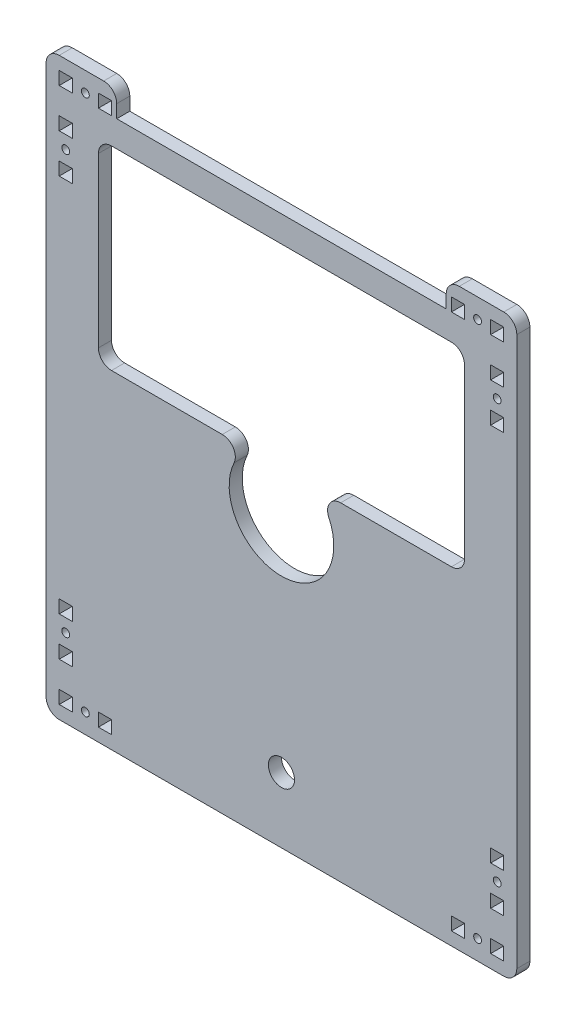
SolidWorks part; units mm, degrees
ref_plane "Front Plane" through (0, 0, 0) normal (0, 0, 1) x (1, 0, 0)
ref_plane "Top Plane" through (0, 0, 0) normal (0, 1, 0) x (1, 0, 0)
ref_plane "Right Plane" through (0, 0, 0) normal (1, 0, 0) x (0, 0, -1)
sketch "Sketch1" plane through (0, 0, 0) normal (0, 0, 1) x (1, 0, 0)
  line L0 (0, 0) -> (187.0096, 0) construction
  line L1 (-90, 110) -> (90, 110) construction
  line L2 (-90, 110) -> (-90, -110)
  line L3 (-90, -110) -> (90, -110)
  line L4 (90, 110) -> (90, -110)
  line L5 (0, 0) -> (0, 134.5508) construction
  line L6 (-90, 102.5) -> (90, 102.5) construction
  line L7 (-70, 90) -> (70, 90)
  line L8 (70, 90) -> (70, 15.6125)
  line L9 (70, 15.6125) -> (-70, 15.6125) construction
  line L10 (-70, 15.6125) -> (-70, 90)
  line L11 (-70, 15.6125) -> (-12.5, 15.6125)
  line L12 (12.5, 15.6125) -> (70, 15.6125)
  line L13 (82.5, 110) -> (82.5, -110) construction
  line L14 (0, 0) -> (0, -110) construction
  line L15 (-90, 110) -> (-63, 110)
  line L16 (-63, 110) -> (-63, 100)
  line L17 (-63, 100) -> (63, 100)
  line L18 (63, 100) -> (63, 110)
  line L19 (63, 110) -> (90, 110)
  arc A0 (-12.5, 15.6125) -> (12.5, 15.6125) centre (0, 0) ccw
  circle A1 centre (0, -85) radius 5
  point P24 (0, 0)
  line B0 (-80, 102.5) -> (-70, 102.5) construction
  line B1 (-80, 105) -> (-85, 105)
  line B2 (-80, 105) -> (-80, 100)
  line B3 (-80, 100) -> (-85, 100)
  line B4 (-85, 105) -> (-85, 100)
  line B5 (-70, 105) -> (-65, 105)
  line B6 (-70, 105) -> (-70, 100)
  line B7 (-70, 100) -> (-65, 100)
  line B8 (-65, 105) -> (-65, 100)
  line B9 (-75, 102.5) -> (-75, 109.4724) construction
  circle B10 centre (-75, 102.5) radius 1.5
  line B11 (-80, -105) -> (-85, -105)
  line B12 (-80, -105) -> (-80, -100)
  line B13 (-80, -100) -> (-85, -100)
  line B14 (-85, -105) -> (-85, -100)
  line B15 (-70, -105) -> (-65, -105)
  line B16 (-70, -105) -> (-70, -100)
  line B17 (-70, -100) -> (-65, -100)
  line B18 (-65, -105) -> (-65, -100)
  circle B19 centre (-75, -102.5) radius 1.5
  line B20 (80, -105) -> (85, -105)
  line B21 (80, -105) -> (80, -100)
  line B22 (80, -100) -> (85, -100)
  line B23 (85, -105) -> (85, -100)
  line B24 (70, -105) -> (65, -105)
  line B25 (70, -105) -> (70, -100)
  line B26 (70, -100) -> (65, -100)
  line B27 (65, -105) -> (65, -100)
  circle B28 centre (75, -102.5) radius 1.5
  line B29 (80, 105) -> (85, 105)
  line B30 (80, 105) -> (80, 100)
  line B31 (80, 100) -> (85, 100)
  line B32 (85, 105) -> (85, 100)
  line B33 (70, 105) -> (65, 105)
  line B34 (70, 105) -> (70, 100)
  line B35 (70, 100) -> (65, 100)
  line B36 (65, 105) -> (65, 100)
  line B37 (75, 102.5) -> (75, 109.4724) construction
  circle B38 centre (75, 102.5) radius 1.5
  line B39 (82.5, 85) -> (82.5, 75) construction
  line B40 (80, 85) -> (80, 90)
  line B41 (80, 85) -> (85, 85)
  line B42 (85, 85) -> (85, 90)
  line B43 (80, 90) -> (85, 90)
  line B44 (80, 75) -> (80, 70)
  line B45 (80, 75) -> (85, 75)
  line B46 (85, 75) -> (85, 70)
  line B47 (80, 70) -> (85, 70)
  line B48 (82.5, 80) -> (75.5276, 80) construction
  circle B49 centre (82.5, 80) radius 1.5
  line B50 (80, -85) -> (80, -90)
  line B51 (80, -85) -> (85, -85)
  line B52 (85, -85) -> (85, -90)
  line B53 (80, -90) -> (85, -90)
  line B54 (80, -75) -> (80, -70)
  line B55 (80, -75) -> (85, -75)
  line B56 (85, -75) -> (85, -70)
  line B57 (80, -70) -> (85, -70)
  circle B58 centre (82.5, -80) radius 1.5
  line B59 (-80, 85) -> (-80, 90)
  line B60 (-80, 85) -> (-85, 85)
  line B61 (-85, 85) -> (-85, 90)
  line B62 (-80, 90) -> (-85, 90)
  line B63 (-80, 75) -> (-80, 70)
  line B64 (-80, 75) -> (-85, 75)
  line B65 (-85, 75) -> (-85, 70)
  line B66 (-80, 70) -> (-85, 70)
  circle B67 centre (-82.5, 80) radius 1.5
  line B68 (-80, -85) -> (-80, -90)
  line B69 (-80, -85) -> (-85, -85)
  line B70 (-85, -85) -> (-85, -90)
  line B71 (-80, -90) -> (-85, -90)
  line B72 (-80, -75) -> (-80, -70)
  line B73 (-80, -75) -> (-85, -75)
  line B74 (-85, -75) -> (-85, -70)
  line B75 (-80, -70) -> (-85, -70)
  circle B76 centre (-82.5, -80) radius 1.5
  dimension "D1" = 150
  dimension "D8" = 20
  dimension "D10" = 10
  dimension "D2" = 7.5
  dimension "D3" = 220
  dimension "D4" = 180
  dimension "D5" = 10
  dimension "D6" = 20
  dimension "D7" = 25
  dimension "D9" = 30
  dimension "D11" = 25
  dimension "D12" = 7.5
  dimension "D13" = 2
sketch_block_instance "Trou M3 plots 5mm-2"
sketch_block "Trou M3 plots 5mm" parameters "D2"=3, "D1"=5, "D3"=5, "D4"=10
sketch_block_instance "Trou M3 plots 5mm-4"
sketch_block_instance "Trou M3 plots 5mm-5"
sketch_block_instance "Trou M3 plots 5mm-6"
sketch_block_instance "Trou M3 plots 5mm-7"
sketch_block_instance "Trou M3 plots 5mm-8"
sketch_block_instance "Trou M3 plots 5mm-9"
sketch_block_instance "Trou M3 plots 5mm-10"
extrude "Boss-Extrude1" add sketch "Sketch1" along normal blind 5
fillet "Fillet1" radius 5 12 edges at (-90, -110, 2.5) (90, -110, 2.5) (-70, 90, 2.5) (-70, 15.6125, 2.5) (70, 15.6125, 2.5) (70, 90, 2.5) (12.5, 15.6125, 2.5) (-12.5, 15.6125, 2.5) (-90, 110, 2.5) (-63, 110, 2.5) (63, 110, 2.5) (90, 110, 2.5)
